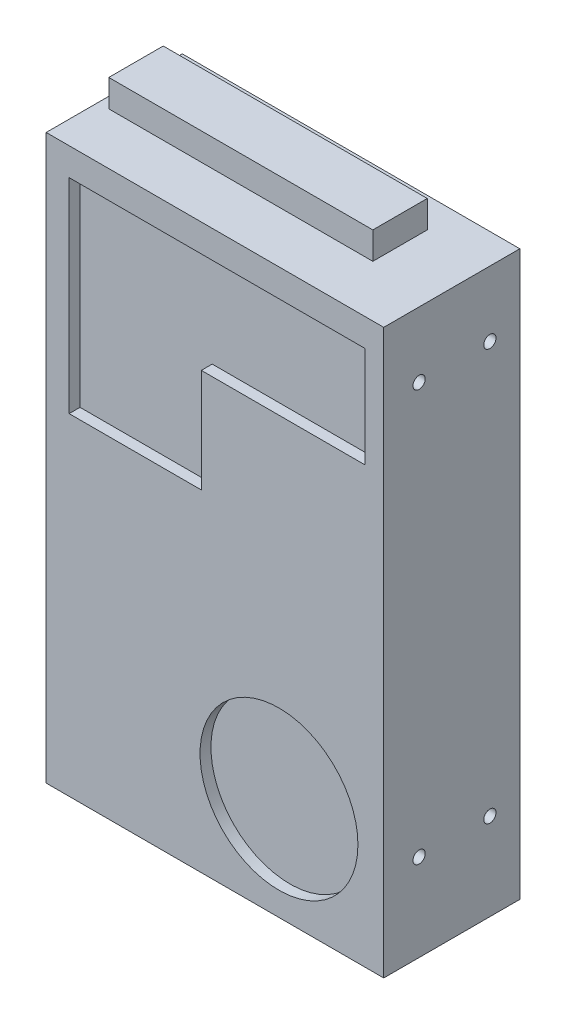
SolidWorks part; units mm, degrees
ref_plane "Front Plane" through (0, 0, 0) normal (0, 0, 1) x (1, 0, 0)
ref_plane "Top Plane" through (0, 0, 0) normal (0, 1, 0) x (1, 0, 0)
ref_plane "Right Plane" through (0, 0, 0) normal (1, 0, 0) x (0, 0, -1)
sketch "Sketch1" plane through (0, 0, 0) normal (0, 0, 1) x (1, 0, 0)
  line L1 (-62, 112.5) -> (62, 112.5)
  line L2 (-62, 112.5) -> (-62, -112.5)
  line L3 (-62, -112.5) -> (62, -112.5)
  line L4 (62, 112.5) -> (62, -112.5)
  line L5 (-62, 112.5) -> (62, -112.5) construction
  line L6 (-62, -112.5) -> (62, 112.5) construction
  point P0 (0, 0)
  dimension "D1" = 124
  dimension "D2" = 225
extrude "Boss-Extrude1" add sketch "Sketch1" along normal blind 50
sketch "Sketch2" plane through (0, 0, 50) normal (0, 0, 1) x (1, 0, 0)
  line L0 (62, 112.5) -> (-62, 112.5) construction
  line L1 (-72.0193, 112.5) -> (70.1235, 112.5)
  line L2 (-72.0193, 112.5) -> (-72.0193, 94.5)
  line L3 (-72.0193, 94.5) -> (70.1235, 94.5)
  line L4 (70.1235, 112.5) -> (70.1235, 94.5)
  dimension "D1" = 18
extrude "Cut-Extrude1" cut sketch "Sketch2" against normal blind 50
sketch "Sketch3" plane through (0, 94.5, 0) normal (0, 1, 0) x (1, 0, 0)
  line L0 (-59, -10) -> (-59, -50) construction
  line L1 (-58, -11) -> (39, -11)
  line L2 (-58, -11) -> (-58, -31)
  line L3 (-58, -31) -> (39, -31)
  line L4 (39, -11) -> (39, -31)
  line L5 (59, -10) -> (59, -50) construction
  line L6 (62, -10) -> (-62, -10) construction
  dimension "D1" = 1
  dimension "D2" = 20
  dimension "D3" = 1
  dimension "D4" = 20
extrude "Boss-Extrude2" add sketch "Sketch3" along normal blind 10
sketch "Sketch4" plane through (0, 0, 50) normal (0, 0, 1) x (1, 0, 0)
  line L3 (-53.557, 84.344) -> (55.0586, 84.344)
  line L5 (-5.0053, 47.3046) -> (55.0586, 47.3046)
  line L6 (55.0586, 84.344) -> (55.0586, 47.3046)
  line L8 (-53.557, 84.344) -> (-53.557, 9.2641)
  line L9 (-53.557, 9.2641) -> (-5.0053, 9.2641)
  line L10 (-5.0053, 47.3046) -> (-5.0053, 9.2641)
  circle A0 centre (23.525, -74.8253) radius 29
  dimension "D3" = 58
extrude "Cut-Extrude3" cut sketch "Sketch4" against normal blind 4
sketch "Sketch5" plane through (0, 0, 0) normal (0, 0, -1) x (-1, 0, 0)
  line L0 (-62, -112.5) -> (-62, 94.5) construction
  line L2 (62, 94.5) -> (-62, 94.5) construction
  circle A0 centre (-25, 70.5) radius 2.25
  circle A1 centre (25, 70.5) radius 2.25
  circle A2 centre (25, -80.5) radius 2.25
  circle A3 centre (-25, -80.5) radius 2.25
  dimension "D1" = 4.5
  dimension "D2" = 37
  dimension "D3" = 24
  dimension "D4" = 2
  dimension "D5" = 2
extrude "Cut-Extrude4" cut sketch "Sketch5" against normal blind 15
sketch "Sketch6" plane through (-62, 0, 0) normal (-1, 0, 0) x (0, 0, 1)
  line L1 (0, 94.5) -> (0, -112.5) construction
  line L2 (50, 94.5) -> (50, -112.5) construction
  line L3 (50, 94.5) -> (0, 94.5) construction
  circle A0 centre (11, 70.5) radius 2.25
  circle A1 centre (37, 70.5) radius 2.25
  circle A2 centre (37, -80.5) radius 2.25
  circle A3 centre (11, -80.5) radius 2.25
  dimension "D1" = 24
  dimension "D2" = 11
  dimension "D5" = 13
  dimension "D3" = 2
  dimension "D4" = 2
extrude "Cut-Extrude5" cut sketch "Sketch6" against normal through all
